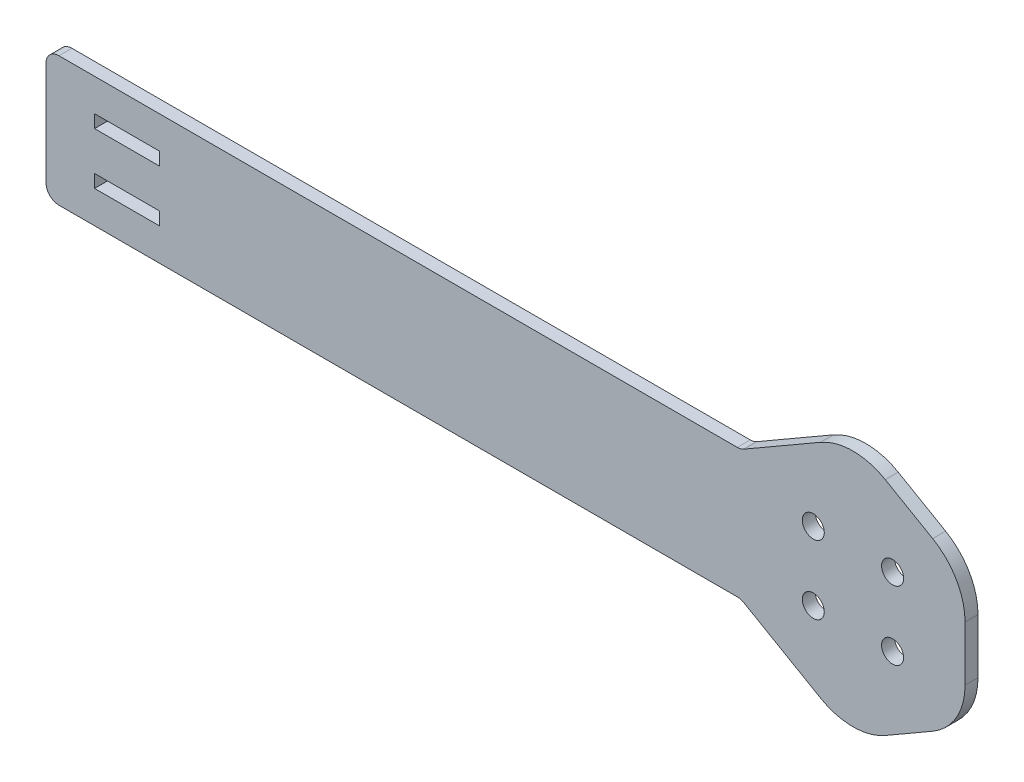
SolidWorks part; units mm, degrees
material "Thornel Mat VMA"
ref_plane "Ön Düzlem" through (0, 0, 0) normal (0, 0, 1) x (1, 0, 0)
ref_plane "Üst Düzlem" through (0, 0, 0) normal (0, 1, 0) x (1, 0, 0)
ref_plane "Sağ Düzlem" through (0, 0, 0) normal (1, 0, 0) x (0, 0, -1)
sketch "Sketch1" plane through (0, 0, 0) normal (0, 0, 1) x (1, 0, 0)
  line L0 (115.9912, -5) -> (0, -5) construction
  line L1 (0, 0) -> (140, 0)
  line L2 (0, 0) -> (0, -40)
  line L3 (0, -40) -> (140, -40)
  line L4 (140, 0) -> (140, -40)
  line L5 (141.972, -10) -> (124.6515, 0)
  line L6 (124.6515, 0) -> (107.331, -10)
  line L7 (107.331, -10) -> (107.331, -30)
  line L8 (107.331, -30) -> (124.6515, -40)
  line L9 (124.6515, -40) -> (141.972, -30)
  line L10 (141.972, -30) -> (141.972, -10)
  line L11 (115.9912, -35) -> (0, -35) construction
  line L12 (124.6515, -20) -> (112.4015, -20) construction
  line L13 (112.4015, -20) -> (118.5265, -20) construction
  line L14 (118.5265, -20) -> (118.5265, -30.6088) construction
  line L15 (118.5265, -20) -> (118.5265, -9.3912) construction
  line L16 (124.6515, -20) -> (136.9015, -20) construction
  line L17 (130.7765, -20) -> (130.7765, -9.3912) construction
  line L18 (130.7765, -20) -> (130.7765, -30.6088) construction
  line L19 (107.331, -10) -> (0, -10)
  line L20 (7.5, -15) -> (22.5, -15) construction
  line L21 (7.5, -15) -> (7.5, -25) construction
  line L22 (7.5, -25) -> (22.5, -25) construction
  line L23 (22.5, -15) -> (22.5, -25) construction
  line L24 (7.5, -15) -> (22.5, -25) construction
  line L25 (7.5, -25) -> (22.5, -15) construction
  line L27 (7.5, -15) -> (17.5, -15)
  line L28 (7.5, -15) -> (7.5, -17)
  line L29 (7.5, -17) -> (17.5, -17)
  line L30 (17.5, -15) -> (17.5, -17)
  line L31 (7.5, -25) -> (17.5, -25)
  line L32 (7.5, -25) -> (7.5, -23)
  line L33 (7.5, -23) -> (17.5, -23)
  line L34 (17.5, -25) -> (17.5, -23)
  line L42 (107.331, -30) -> (0, -30)
  circle A0 centre (124.6515, -20) radius 17.3205 construction
  circle A1 centre (124.6515, -20) radius 12.25
  circle A2 centre (118.5265, -14.6956) radius 1.7
  circle A3 centre (130.7765, -14.6956) radius 1.7
  circle A4 centre (130.7765, -25.3044) radius 1.7
  circle A5 centre (118.5265, -25.3044) radius 1.7
  point P34 (15, -20)
  dimension "D6" = 24.5
  dimension "D7" = 3.4
  dimension "D8" = 15
  dimension "D1" = 140
  dimension "D2" = 40
  dimension "D3" = 0
  dimension "D4" = 0
  dimension "D5" = 360
  dimension "D9" = 10
  dimension "D10" = 10
  dimension "D11" = 7.5
  dimension "D12" = 2
  dimension "D13" = 10
  dimension "D14" = 10
  dimension "D15" = 2
extrude "Boss-Extrude3" add sketch "Sketch1" along normal blind 2 contours L42 L7 L19 L2 L34 L31 L32 L33 L27 L30 L29 L28 | L8 L9 L4 L5 L6 L7 A1 | A1 A5 A4 A3 A2 | L9 L10 L5 L4
fillet "Fillet5" radius 10 1 edges at (124.6515, 0, 1)
fillet "Fillet6" radius 10 1 edges at (141.972, -10, 1)
fillet "Fillet7" radius 10 1 edges at (141.972, -30, 1)
fillet "Fillet8" radius 10 1 edges at (124.6515, -40, 1)
fillet "Fillet14" radius 2 2 edges at (0, -30, 1) (0, -10, 1)
fillet "Fillet15" radius 2 1 edges at (107.331, -10, 1)
fillet "Fillet16" radius 2 1 edges at (107.331, -30, 1)
